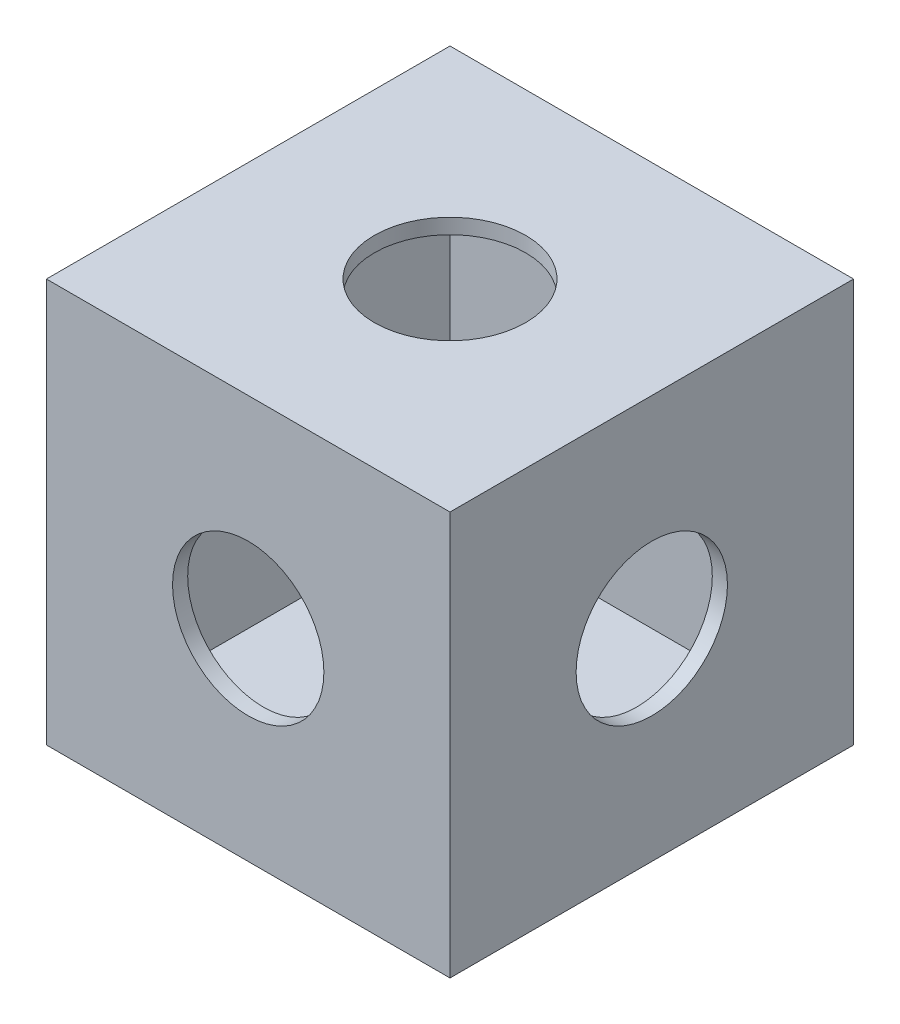
SolidWorks part; units mm, degrees
ref_plane "Front Plane" through (0, 0, 0) normal (0, 0, 1) x (1, 0, 0)
ref_plane "Top Plane" through (0, 0, 0) normal (0, 1, 0) x (1, 0, 0)
ref_plane "Right Plane" through (0, 0, 0) normal (1, 0, 0) x (0, 0, -1)
sketch "Sketch1" plane through (0, 0, 0) normal (0, 1, 0) x (1, 0, 0)
  line L1 (0, 0) -> (40, 0)
  line L2 (0, 0) -> (0, 40)
  line L3 (0, 40) -> (40, 40)
  line L4 (40, 0) -> (40, 40)
extrude "Boss-Extrude2" add sketch "Sketch1" against normal blind 1.5
sketch "Sketch2" plane through (0, 0, 0) normal (0, 1, 0) x (1, 0, 0)
  line L1 (0, 0) -> (40, 0)
  line L2 (0, 0) -> (0, 40)
  line L3 (0, 40) -> (40, 40)
  line L4 (40, 0) -> (40, 40)
  line L5 (1.5, 1.5) -> (38.5, 1.5)
  line L6 (1.5, 1.5) -> (1.5, 38.5)
  line L7 (1.5, 38.5) -> (38.5, 38.5)
  line L8 (38.5, 1.5) -> (38.5, 38.5)
extrude "Boss-Extrude3" add sketch "Sketch2" along normal blind 37
sketch "Sketch3" plane through (0, 37, 0) normal (0, 1, 0) x (1, 0, 0)
  line L1 (0, 0) -> (40, 0)
  line L2 (0, 0) -> (0, 40)
  line L3 (0, 40) -> (40, 40)
  line L4 (40, 0) -> (40, 40)
extrude "Boss-Extrude4" add sketch "Sketch3" along normal blind 1.5
sketch "Sketch4" plane through (0, 38.5, 0) normal (0, 1, 0) x (1, 0, 0)
  circle A0 centre (20, 20) radius 7.5
extrude "Cut-Extrude1" cut sketch "Sketch4" against normal through all
sketch "Sketch5" plane through (40, 0, 0) normal (1, 0, 0) x (0, 0, -1)
  circle A0 centre (20, 18.5) radius 7.5
extrude "Cut-Extrude2" cut sketch "Sketch5" against normal through all
sketch "Sketch6" plane through (0, 0, 0) normal (0, 0, 1) x (1, 0, 0)
  circle A0 centre (20, 18.5) radius 7.5
extrude "Cut-Extrude3" cut sketch "Sketch6" against normal through all
